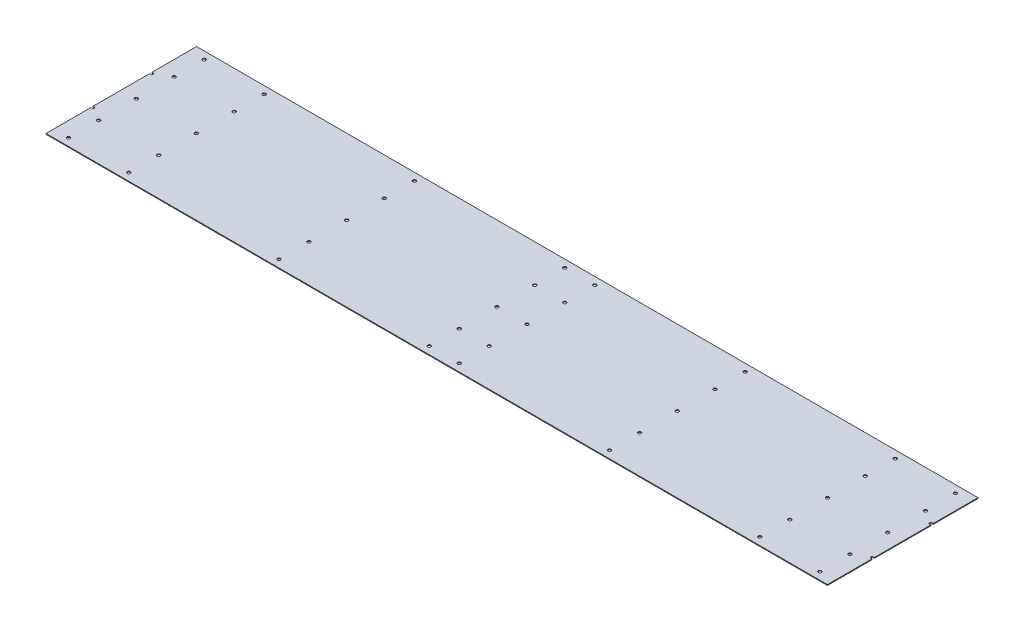
SolidWorks part; units mm, degrees
ref_plane "Front Plane" through (0, 0, 0) normal (0, 0, 1) x (1, 0, 0)
ref_plane "Top Plane" through (0, 0, 0) normal (0, 1, 0) x (1, 0, 0)
ref_plane "Right Plane" through (0, 0, 0) normal (1, 0, 0) x (0, 0, -1)
sketch "Sketch1" plane through (0, 0, 0) normal (0, 1, 0) x (1, 0, 0)
  line L0 (-500, -40.7) -> (-500, -100.2)
  line L1 (-500, -100.2) -> (540, -100.2)
  line L2 (540, -100.2) -> (540, -40.7)
  line L3 (540, -40.7) -> (-500, -40.7) construction
  line L4 (0, 0) -> (-497, 0) construction
  line L5 (-500, -40.7) -> (-497, -40.7)
  line L7 (-497, 40.7) -> (-500, 40.7)
  line L8 (-500, 40.7) -> (-500, 100.2)
  line L9 (-500, 100.2) -> (540, 100.2)
  line L10 (540, 100.2) -> (540, 40.7)
  line L11 (540, 40.7) -> (537, 40.7)
  line L13 (537, -40.7) -> (540, -40.7)
  line L14 (0, 50.2) -> (520, 50.2) construction
  line L15 (-497, 40.7) -> (-497, 37.7)
  line L16 (-497, 40.7) -> (537, 40.7) construction
  line L17 (537, 40.7) -> (537, -40.7) construction
  line L18 (-497, 40.7) -> (-497, -40.7) construction
  line L19 (-497, 37.7) -> (-500, 37.7)
  line L20 (-500, 37.7) -> (-500, -37.7)
  line L21 (-500, -37.7) -> (-497, -37.7)
  line L22 (-497, -37.7) -> (-497, -40.7)
  line L23 (537, 40.7) -> (537, 37.7)
  line L24 (537, 37.7) -> (540, 37.7)
  line L25 (540, 37.7) -> (540, -37.7)
  line L26 (540, -37.7) -> (537, -37.7)
  line L27 (537, -37.7) -> (537, -40.7)
  line L28 (540, 0) -> (537, 0) construction
  line L29 (520, 50.2) -> (520, -50.2) construction
  line L30 (-497, 0) -> (-500, 0) construction
  line L31 (0, 50.2) -> (0, -50.2) construction
  line L32 (520, -50.2) -> (0, -50.2) construction
  line L33 (0, 50.2) -> (0, 90.2) construction
  line L34 (0, 90.2) -> (520, 90.2) construction
  line L35 (520, 90.2) -> (520, 50.2) construction
  line L36 (520, -50.2) -> (520, -90.2) construction
  line L37 (520, -90.2) -> (0, -90.2) construction
  line L38 (0, -90.2) -> (0, -50.2) construction
  line L39 (0, 0) -> (520, 0) construction
  line L40 (-200, 90.2) -> (-200, 50.2) construction
  line L41 (-200, 50.2) -> (-200, 0) construction
  line L42 (-200, 0) -> (-200, -50.2) construction
  line L43 (-200, -50.2) -> (-200, -90.2) construction
  line L44 (40, 90.2) -> (40, -90.2) construction
  line L45 (-400, 90.2) -> (-480, 90.2) construction
  line L46 (-480, 90.2) -> (-480, -90.2) construction
  line L47 (-480, -90.2) -> (-400, -90.2) construction
  line L48 (-400, -90.2) -> (-400, 90.2) construction
  line L49 (-400, 90.2) -> (0, 90.2) construction
  line L50 (440, 90.2) -> (440, -90.2) construction
  line L51 (-400, 50.2) -> (0, 50.2) construction
  line L52 (440, -90.2) -> (520, -90.2) construction
  line L53 (-400, -50.2) -> (0, -50.2) construction
  line L55 (-480, -90.2) -> (0, -90.2) construction
  line L56 (440, -50.2) -> (520, -50.2) construction
  line L58 (440, 0) -> (520, 0) construction
  line L60 (440, 50.2) -> (520, 50.2) construction
  line L62 (440, 90.2) -> (520, 90.2) construction
  circle A0 centre (0, -50.2) radius 2.15
  circle A30 centre (0, 50.2) radius 2.15
  circle A31 centre (0, -90.2) radius 2.15
  circle A32 centre (0, 90.2) radius 2.15
  circle A33 centre (-200, -90.2) radius 2.15
  circle A34 centre (-200, -50.2) radius 2.15
  circle A35 centre (-200, 50.2) radius 2.15
  circle A36 centre (-200, 90.2) radius 2.15
  circle A53 centre (0, 0) radius 2.15
  circle A55 centre (-200, 0) radius 2.15
  circle A56 centre (-400, 0) radius 2.15
  circle A57 centre (-400, -90.2) radius 2.15
  circle A58 centre (-400, -50.2) radius 2.15
  circle A59 centre (-400, 50.2) radius 2.15
  circle A60 centre (-400, 90.2) radius 2.15
  circle A61 centre (40, -90.2) radius 2.15
  circle A62 centre (40, -50.2) radius 2.15
  circle A63 centre (40, 0) radius 2.15
  circle A64 centre (40, 50.2) radius 2.15
  circle A65 centre (40, 90.2) radius 2.15
  circle A66 centre (520, 90.2) radius 2.15
  circle A67 centre (520, 50.2) radius 2.15
  circle A68 centre (520, 0) radius 2.15
  circle A69 centre (520, -50.2) radius 2.15
  circle A70 centre (520, -90.2) radius 2.15
  circle A71 centre (240, -90.2) radius 2.15
  circle A72 centre (240, -50.2) radius 2.15
  circle A73 centre (240, 0) radius 2.15
  circle A74 centre (240, 50.2) radius 2.15
  circle A75 centre (240, 90.2) radius 2.15
  circle A76 centre (440, -90.2) radius 2.15
  circle A77 centre (440, -50.2) radius 2.15
  circle A78 centre (440, 0) radius 2.15
  circle A79 centre (440, 50.2) radius 2.15
  circle A80 centre (440, 90.2) radius 2.15
  circle A81 centre (-480, 90.2) radius 2.15
  circle A82 centre (-480, 50.2) radius 2.15
  circle A83 centre (-480, 0) radius 2.15
  circle A84 centre (-480, -90.2) radius 2.15
  circle A85 centre (-480, -50.2) radius 2.15
  dimension "D12" = 4.3
  dimension "D13" = 12.5
  dimension "D11" = 200
  dimension "D2" = 75.4
  dimension "D3" = 3
  dimension "D6" = 10
  dimension "D7" = 40
  dimension "D16" = 12.5
  dimension "D8" = 3
  dimension "D4" = 40
  dimension "D17" = 200
  dimension "D5" = 80
  dimension "D15" = 20
  dimension "D18" = 80
  dimension "D19" = 20
  dimension "D20" = 1040
  dimension "D9" = 3
  dimension "D14" = 3
  dimension "D10" = 3
extrude "Boss-Extrude1" add sketch "Sketch1" along normal blind 1
equation "\"skin_sheetmetal_thickness\"= 0.80"
equation "\"base_width_skin_spacer\" = \"base_width_skin_target_width\" - 4 * \"skin_sheetmetal_thickness\" - 2 * \"base_width_skin_target_bend_radius\""
equation "\"base_width_skin_inner\" = \"base_width_skin_spacer\" + 2 * \"skin_sheetmetal_thickness\""
equation "\"base_width_skin_outer\" = \"base_width_skin_inner\" + 2 * \"skin_sheetmetal_thickness\""
equation "\"bend_cut_width\"= 3"
equation "\"bend_cut_length\"= 3"
equation "\"bend_offset_inner\"= 12.5"
equation "\"bend_offset_outer\" = \"bend_offset_inner\" + \"skin_sheetmetal_thickness\""
equation "\"border_offset_ends\"= 20"
equation "\"border_offset_sides\"= 10"
equation "\"border_offset_flange_horiz\"= 10"
equation "\"rivet_size\"= 4.3"
equation "\"rivet_offset_ends\"= \"rivet_spacing_horiz\"/2 - \"border_offset_ends\""
equation "\"rivet_spacing_horiz\"= 200"
equation "\"rivet_spacing_vert\"= 40"
equation "\"rivet_spacing_offset_right\"= 40"
equation "\"base_length\"= 200"
equation "\"base_width_skin_spacer_length\" = 430"
equation "\"bend_offset_spacer_tab\"= 21.0"
equation "\"D2@Sketch1\"=\"base_width_skin_inner\""
equation "\"D3@Sketch1\"=\"bend_cut_length\""
equation "\"D8@Sketch1\"=\"bend_cut_width\""
equation "\"D16@Sketch1\"=\"bend_offset_inner\""
equation "\"D7@Sketch1\"=\"rivet_spacing_vert\""
equation "\"D12@Sketch1\"=\"rivet_size\""
equation "\"D6@Sketch1\"=\"border_offset_flange_horiz\""
equation "\"D11@Sketch1\"=\"rivet_spacing_horiz\""
equation "\"D4@Sketch1\"=\"rivet_spacing_offset_right\""
equation "\"D17@Sketch1\"=\"rivet_spacing_horiz\""
equation "\"D5@Sketch1\"=\"rivet_offset_ends\""
equation "\"D15@Sketch1\"=\"border_offset_ends\""
equation "\"D18@Sketch1\"=\"rivet_offset_ends\""
equation "\"D19@Sketch1\"=\"border_offset_ends\""
equation "\"base_width_skin_target_width\" = 80"
equation "\"base_width_skin_target_bend_radius\" = 1.5"
